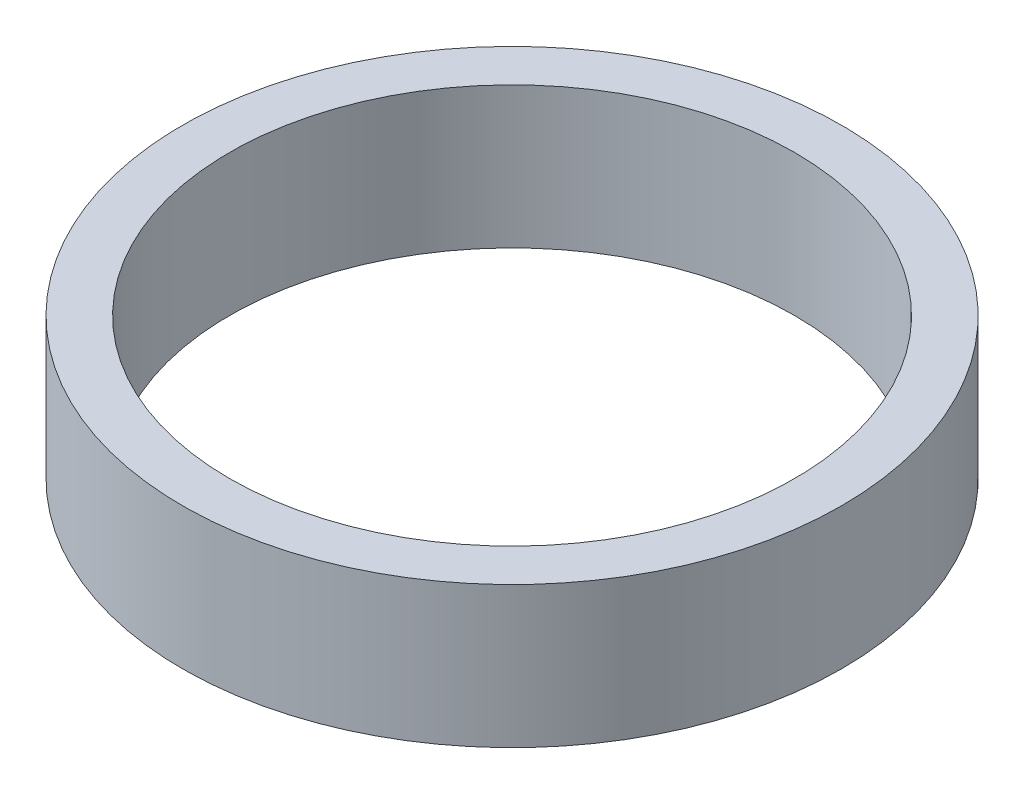
SolidWorks part; units mm, degrees
ref_plane "Front Plane" through (0, 0, 0) normal (0, 0, 1) x (1, 0, 0)
ref_plane "Top Plane" through (0, 0, 0) normal (0, 1, 0) x (1, 0, 0)
ref_plane "Right Plane" through (0, 0, 0) normal (1, 0, 0) x (0, 0, -1)
sketch "Sketch1" plane through (0, 0, 0) normal (0, 1, 0) x (1, 0, 0)
  circle A0 centre (0, 0) radius 6
  dimension "D1" = 12
extrude "Extrude-Thin1" add sketch "Sketch1" along normal blind 3 thin
